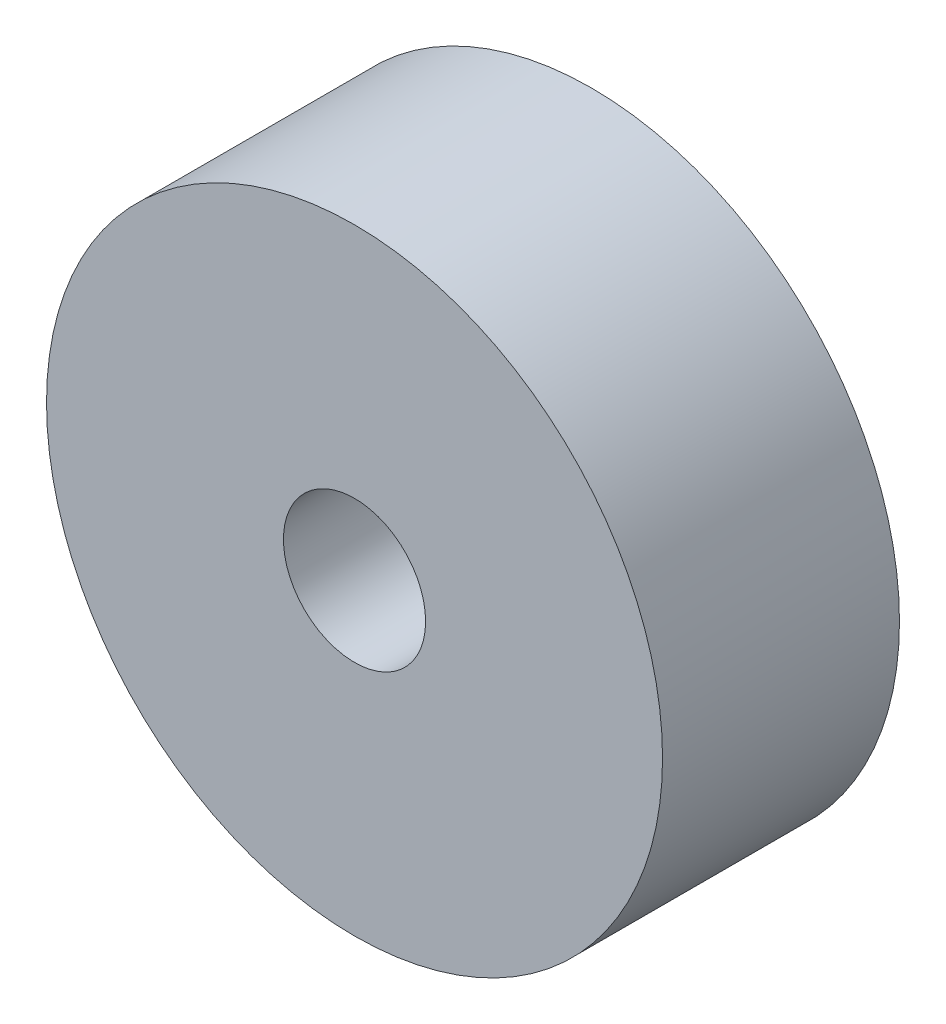
SolidWorks part; units mm, degrees
ref_plane "前视基准面" through (0, 0, 0) normal (0, 0, 1) x (1, 0, 0)
ref_plane "上视基准面" through (0, 0, 0) normal (0, 1, 0) x (1, 0, 0)
ref_plane "右视基准面" through (0, 0, 0) normal (1, 0, 0) x (0, 0, -1)
sketch "草图1" plane through (0, 0, 0) normal (0, 0, 1) x (1, 0, 0)
  circle A0 centre (0, 0) radius 6
  circle A1 centre (0, 0) radius 26
  dimension "D1" = 12
  dimension "D2" = 52
extrude "凸台-拉伸1" add sketch "草图1" along normal blind 20
